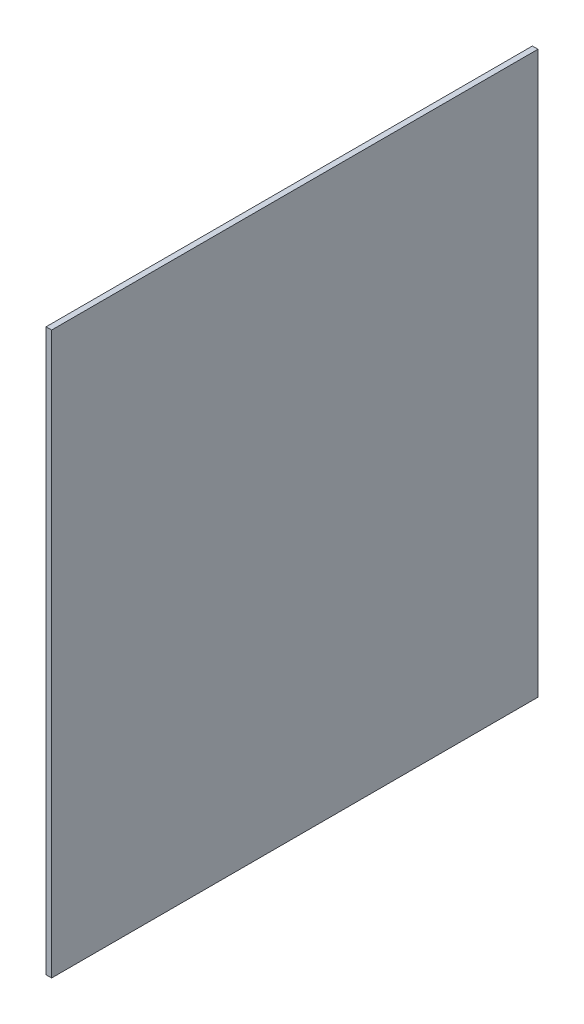
SolidWorks part; units mm, degrees
ref_plane "Front Plane" through (0, 0, 0) normal (0, 0, 1) x (1, 0, 0)
ref_plane "Top Plane" through (0, 0, 0) normal (0, 1, 0) x (1, 0, 0)
ref_plane "Right Plane" through (0, 0, 0) normal (1, 0, 0) x (0, 0, -1)
sketch "Sketch1" plane through (0, 0, 0) normal (1, 0, 0) x (0, 0, -1)
  line L1 (-248.1452, 16.0645) -> (11.8548, 16.0645)
  line L2 (-248.1452, 16.0645) -> (-248.1452, -283.9355)
  line L3 (-248.1452, -283.9355) -> (11.8548, -283.9355)
  line L4 (11.8548, 16.0645) -> (11.8548, -283.9355)
  dimension "D1" = 300
  dimension "D2" = 260
extrude "Boss-Extrude2" add sketch "Sketch1" along normal blind 3
